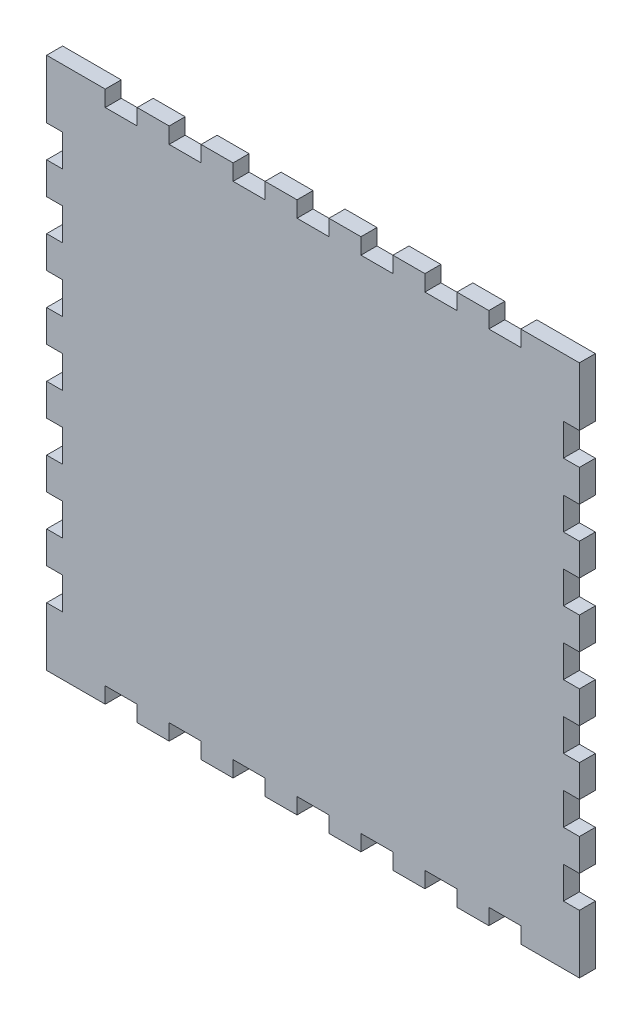
SolidWorks part; units mm, degrees
ref_plane "Front Plane" through (0, 0, 0) normal (0, 0, 1) x (1, 0, 0)
ref_plane "Top Plane" through (0, 0, 0) normal (0, 1, 0) x (1, 0, 0)
ref_plane "Right Plane" through (0, 0, 0) normal (1, 0, 0) x (0, 0, -1)
sketch "Model" plane through (0, 0, 0) normal (0, 0, 1) x (1, 0, 0)
  line L0 (0, 203) -> (0, 181)
  line L1 (0, 181) -> (6, 181)
  line L2 (6, 181) -> (6, 169)
  line L3 (6, 169) -> (0, 169)
  line L4 (0, 169) -> (0, 157)
  line L5 (0, 157) -> (6, 157)
  line L6 (6, 157) -> (6, 145)
  line L7 (6, 145) -> (0, 145)
  line L8 (0, 145) -> (0, 133)
  line L9 (0, 133) -> (6, 133)
  line L10 (6, 133) -> (6, 121)
  line L11 (6, 121) -> (0, 121)
  line L12 (0, 121) -> (0, 109)
  line L13 (0, 109) -> (6, 109)
  line L14 (6, 109) -> (6, 97)
  line L15 (6, 97) -> (0, 97)
  line L16 (0, 97) -> (0, 85)
  line L17 (0, 85) -> (6, 85)
  line L18 (6, 85) -> (6, 73)
  line L19 (6, 73) -> (0, 73)
  line L20 (0, 73) -> (0, 61)
  line L21 (0, 61) -> (6, 61)
  line L22 (6, 61) -> (6, 49)
  line L23 (6, 49) -> (0, 49)
  line L24 (0, 49) -> (0, 37)
  line L25 (0, 37) -> (6, 37)
  line L26 (6, 37) -> (6, 25)
  line L27 (6, 25) -> (0, 25)
  line L28 (0, 25) -> (0, 13)
  line L29 (0, 13) -> (0, 3)
  line L30 (0, 3) -> (22, 3)
  line L31 (22, 3) -> (22, 9)
  line L32 (22, 9) -> (34, 9)
  line L33 (34, 9) -> (34, 3)
  line L34 (34, 3) -> (46, 3)
  line L35 (46, 3) -> (46, 9)
  line L36 (46, 9) -> (58, 9)
  line L37 (58, 9) -> (58, 3)
  line L38 (58, 3) -> (70, 3)
  line L39 (70, 3) -> (70, 9)
  line L40 (70, 9) -> (82, 9)
  line L41 (82, 9) -> (82, 3)
  line L42 (82, 3) -> (94, 3)
  line L43 (94, 3) -> (94, 9)
  line L44 (94, 9) -> (106, 9)
  line L45 (106, 9) -> (106, 3)
  line L46 (106, 3) -> (118, 3)
  line L47 (118, 3) -> (118, 9)
  line L48 (118, 9) -> (130, 9)
  line L49 (130, 9) -> (130, 3)
  line L50 (130, 3) -> (142, 3)
  line L51 (142, 3) -> (142, 9)
  line L52 (142, 9) -> (154, 9)
  line L53 (154, 9) -> (154, 3)
  line L54 (154, 3) -> (166, 3)
  line L55 (166, 3) -> (166, 9)
  line L56 (166, 9) -> (178, 9)
  line L57 (178, 9) -> (178, 3)
  line L58 (178, 3) -> (190, 3)
  line L59 (190, 3) -> (200, 3)
  line L60 (200, 3) -> (200, 25)
  line L61 (200, 25) -> (194, 25)
  line L62 (194, 25) -> (194, 37)
  line L63 (194, 37) -> (200, 37)
  line L64 (200, 37) -> (200, 49)
  line L65 (200, 49) -> (194, 49)
  line L66 (194, 49) -> (194, 61)
  line L67 (194, 61) -> (200, 61)
  line L68 (200, 61) -> (200, 73)
  line L69 (200, 73) -> (194, 73)
  line L70 (194, 73) -> (194, 85)
  line L71 (194, 85) -> (200, 85)
  line L72 (200, 85) -> (200, 97)
  line L73 (200, 97) -> (194, 97)
  line L74 (194, 97) -> (194, 109)
  line L75 (194, 109) -> (200, 109)
  line L76 (200, 109) -> (200, 121)
  line L77 (200, 121) -> (194, 121)
  line L78 (194, 121) -> (194, 133)
  line L79 (194, 133) -> (200, 133)
  line L80 (200, 133) -> (200, 145)
  line L81 (200, 145) -> (194, 145)
  line L82 (194, 145) -> (194, 157)
  line L83 (194, 157) -> (200, 157)
  line L84 (200, 157) -> (200, 169)
  line L85 (200, 169) -> (194, 169)
  line L86 (194, 169) -> (194, 181)
  line L87 (194, 181) -> (200, 181)
  line L88 (200, 181) -> (200, 193)
  line L89 (200, 193) -> (200, 203)
  line L90 (200, 203) -> (178, 203)
  line L91 (178, 203) -> (178, 197)
  line L92 (178, 197) -> (166, 197)
  line L93 (166, 197) -> (166, 203)
  line L94 (166, 203) -> (154, 203)
  line L95 (154, 203) -> (154, 197)
  line L96 (154, 197) -> (142, 197)
  line L97 (142, 197) -> (142, 203)
  line L98 (142, 203) -> (130, 203)
  line L99 (130, 203) -> (130, 197)
  line L100 (130, 197) -> (118, 197)
  line L101 (118, 197) -> (118, 203)
  line L102 (118, 203) -> (106, 203)
  line L103 (106, 203) -> (106, 197)
  line L104 (106, 197) -> (94, 197)
  line L105 (94, 197) -> (94, 203)
  line L106 (94, 203) -> (82, 203)
  line L107 (82, 203) -> (82, 197)
  line L108 (82, 197) -> (70, 197)
  line L109 (70, 197) -> (70, 203)
  line L110 (70, 203) -> (58, 203)
  line L111 (58, 203) -> (58, 197)
  line L112 (58, 197) -> (46, 197)
  line L113 (46, 197) -> (46, 203)
  line L114 (46, 203) -> (34, 203)
  line L115 (34, 203) -> (34, 197)
  line L116 (34, 197) -> (22, 197)
  line L117 (22, 197) -> (22, 203)
  line L118 (22, 203) -> (10, 203)
  line L119 (10, 203) -> (0, 203)
extrude "Boss-Extrude1" add sketch "Model" along normal blind 6
